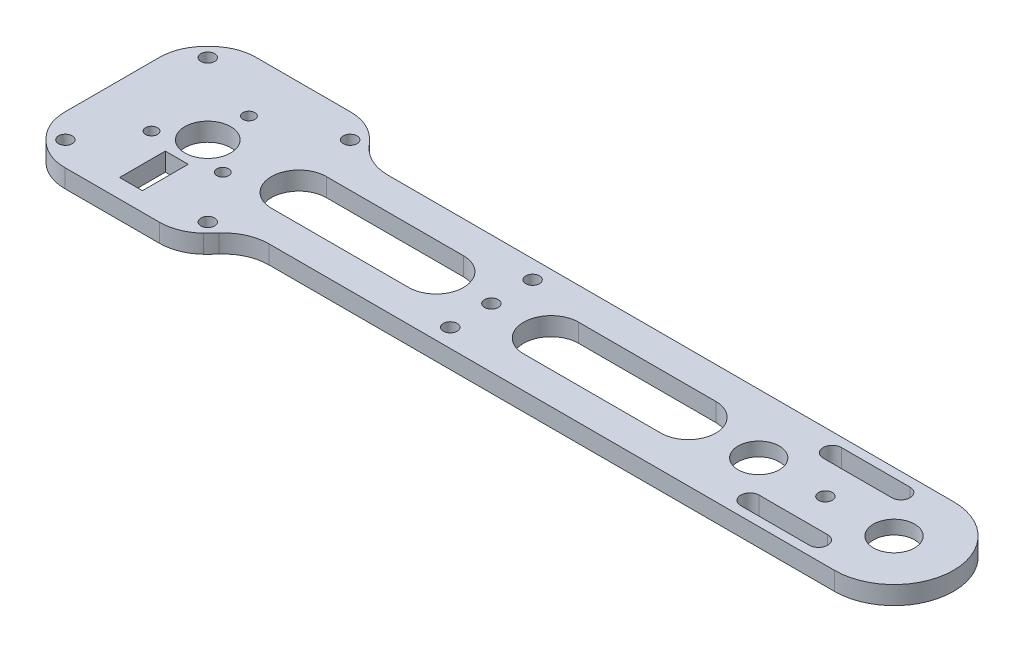
SolidWorks part; units mm, degrees
material "6061-O (SS)"
ref_plane "前视基准面" through (0, 0, 0) normal (0, 0, 1) x (1, 0, 0)
ref_plane "上视基准面" through (0, 0, 0) normal (0, 1, 0) x (1, 0, 0)
ref_plane "右视基准面" through (0, 0, 0) normal (1, 0, 0) x (0, 0, -1)
other "Configuration Table"
sketch "草图1" plane through (0, 0, 0) normal (0, 1, 0) x (1, 0, 0)
  line L0 (0, 0) -> (150, 0) construction
  line L6 (-2.5, -16.7734) -> (-2.5, -6.7734)
  line L7 (-2.5, -16.7734) -> (2.5, -16.7734)
  line L8 (2.5, -16.7734) -> (2.5, -6.7734)
  line L9 (-2.5, -6.7734) -> (2.5, -6.7734)
  line L10 (-2.5, -16.7734) -> (2.5, -6.7734) construction
  line L11 (2.5, -16.7734) -> (-2.5, -6.7734) construction
  line L21 (49.9121, 0) -> (19.9121, 0) construction
  line L22 (49.9121, -6) -> (19.9121, -6)
  line L23 (49.9121, 6) -> (19.9121, 6)
  line L24 (105.0415, 0) -> (75.0415, 0) construction
  line L25 (105.0415, -6) -> (75.0415, -6)
  line L26 (105.0415, 6) -> (75.0415, 6)
  line L27 (150, 13) -> (21.3542, 13)
  line L28 (150, -13) -> (21.3542, -13)
  line L29 (-13.7487, 20.88) -> (13.7487, 20.88)
  line L31 (13.7487, -20.88) -> (-13.7487, -20.88)
  line L32 (-20.88, -13.7487) -> (-20.88, 13.7487)
  line L33 (20.88, 13.7487) -> (20.88, -13.7487) [skipped]
  circle A2 centre (0, 0) radius 5
  circle A3 centre (150, 0) radius 4.505
  circle A4 centre (120.4195, 0) radius 4.505
  circle A6 centre (0, 9) radius 1.3
  circle A7 centre (7.7942, -4.5) radius 1.3
  circle A8 centre (-7.7942, -4.5) radius 1.3
  arc A15 (150, -13) -> (150, 13) centre (150, 0) ccw
  arc A16 (49.9121, -6) -> (49.9121, 6) centre (49.9121, 0) ccw
  arc A17 (19.9121, 6) -> (19.9121, -6) centre (19.9121, 0) ccw
  arc A18 (105.0415, -6) -> (105.0415, 6) centre (105.0415, 0) ccw
  arc A19 (75.0415, 6) -> (75.0415, -6) centre (75.0415, 0) ccw
  circle A20 centre (135, 0) radius 1.5
  circle A21 centre (62, 0) radius 1.5
  circle A22 centre (62, 9) radius 1.5
  circle A23 centre (62, -9) radius 1.5
  arc A25 (21.3542, 13) -> (13.7487, 20.88) centre (0, 0) ccw
  circle A26 centre (-15.5563, 15.5563) radius 1.5
  circle A27 centre (15.5563, 15.5563) radius 1.5
  circle A28 centre (15.5563, -15.5563) radius 1.5
  circle A29 centre (-15.5563, -15.5563) radius 1.5
  arc A30 (-13.7487, 20.88) -> (-20.88, 13.7487) centre (0, 0) ccw
  arc A31 (-20.88, -13.7487) -> (-13.7487, -20.88) centre (0, 0) ccw
  arc A32 (13.7487, -20.88) -> (21.3542, -13) centre (0, 0) ccw
  point P5 (75, 0)
  point P9 (9.7734, 0)
  point P20 (34.9121, 0)
  point P23 (0, 0)
  point P35 (90.0415, 0)
  point P59 (0, 0)
  point P68 (0, 0)
  dimension "D1" = 3
  dimension "D2" = 4
  dimension "D3" = 4
extrude "凸台-拉伸1" add sketch "草图1" along normal blind 4
sketch "草图2" plane through (0, 0, 0) normal (0, -1, 0) x (1, 0, 0)
  circle A0 centre (150, 0) radius 6.01
  circle A1 centre (120.4195, 0) radius 6.01
extrude "切除-拉伸1" cut sketch "草图2" against normal blind 1
ref_point "点1"
sketch "草图4" plane through (0, 4, 0) normal (0, 1, 0) x (1, 0, 0)
  line L0 (127.5, 9) -> (142.5, 9) construction
  line L1 (127.5, 11) -> (142.5, 11)
  line L2 (127.5, 7) -> (142.5, 7)
  line L4 (127.5, -9) -> (142.5, -9) construction
  line L5 (127.5, -11) -> (142.5, -11)
  line L6 (127.5, -7) -> (142.5, -7)
  arc A0 (127.5, 11) -> (127.5, 7) centre (127.5, 9) ccw
  arc A1 (142.5, 7) -> (142.5, 11) centre (142.5, 9) ccw
  arc A2 (127.5, -11) -> (127.5, -7) centre (127.5, -9) cw
  arc A3 (142.5, -7) -> (142.5, -11) centre (142.5, -9) cw
  point P2 (135, 9)
  point P13 (135, -9)
extrude "切除-拉伸4" cut sketch "草图4" against normal blind 4
fillet "圆角1" radius 10 8 edges at (21.3542, 2, 13) (13.7487, 2, 20.88) (-20.88, 2, 13.7487) (-20.88, 2, -13.7487) (-13.7487, 2, -20.88) (13.7487, 2, -20.88) (21.3542, 2, -13) (-13.7487, 2, 20.88)
